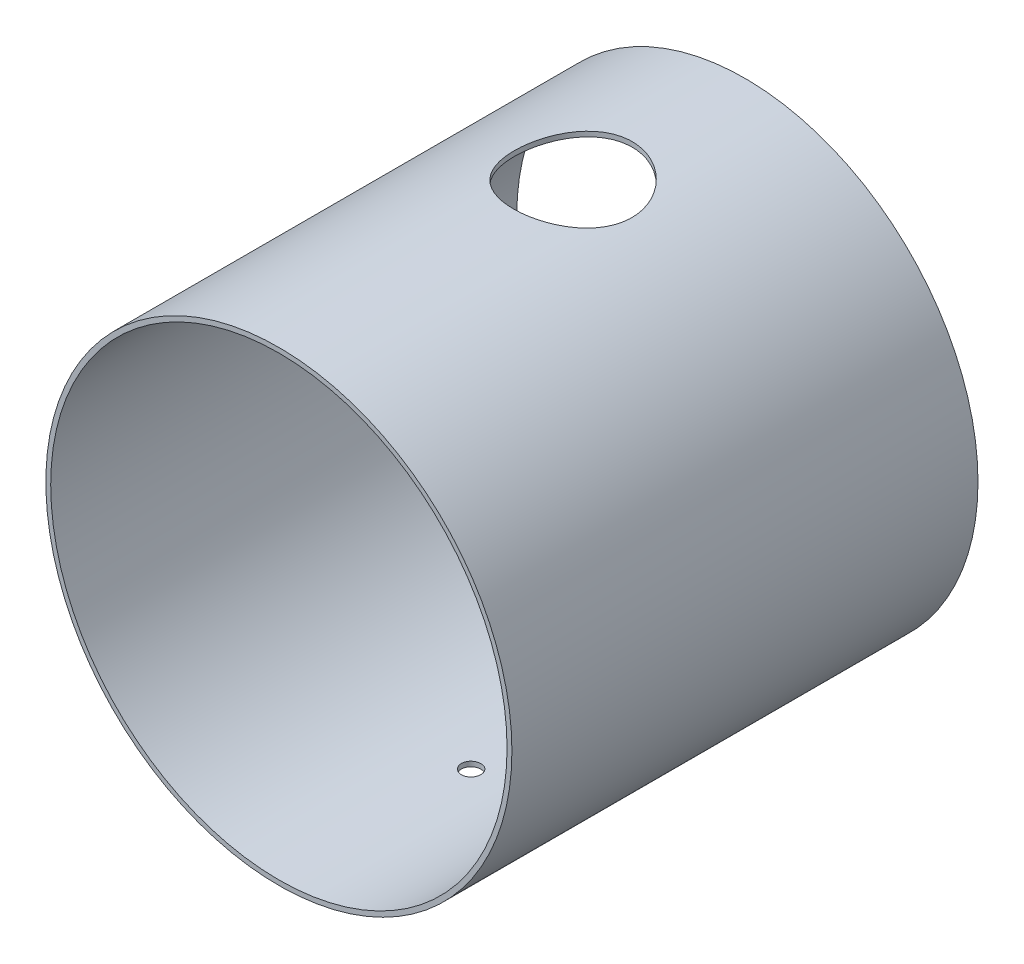
SolidWorks part; units mm, degrees
ref_plane "Front Plane" through (0, 0, 0) normal (0, 0, 1) x (1, 0, 0)
ref_plane "Top Plane" through (0, 0, 0) normal (0, 1, 0) x (1, 0, 0)
ref_plane "Right Plane" through (0, 0, 0) normal (1, 0, 0) x (0, 0, -1)
sketch "Sketch1" plane through (0, 0, 0) normal (0, 0, 1) x (1, 0, 0)
  line L0 (-149.225, 0) -> (-152.4, 0) construction
  circle A0 centre (0, 0) radius 149.225
  circle A1 centre (0, 0) radius 152.4
  dimension "OD" = 304.8
  dimension "ID" = 298.45
  dimension "Wall Thickness" = 3.175
sketch "Sketch2" plane through (0, 0, 0) normal (1, 0, 0) x (0, 0, -1)
  line L0 (-152.4, -152.4) -> (152.4, -152.4)
  line L1 (-76.2, 152.4) -> (76.2, 152.4) construction
  line L3 (-152.4, 152.4) -> (152.4, 152.4)
  point P2 (0, -152.4)
  point P3 (0, 152.4)
  point P10 (-76.2, 152.4)
  point P12 (76.2, 152.4)
  dimension "Length" = 304.8
  dimension "OD" = 304.8
  dimension "D1" = 152.4
sketch "Sketch3" plane through (0, 0, 0) normal (0, 0, 1) x (1, 0, 0)
  circle A0 centre (0, 0) radius 149.225 construction
  circle A1 centre (0, 0) radius 152.4 construction
  circle A2 centre (0, 0) radius 149.225
  circle A3 centre (0, 0) radius 152.4
extrude "Boss-Extrude1" add sketch "Sketch3" along normal mid plane 304.8
hole_wizard "Ø1.0mm Dowel Hole1" positions "3DSketch1" profile "Sketch4" hole size "Ø1.0" standard "ANSI Metric"
sketch3d "3DSketch1"
  point P0 (-1.2376, 152.395, -41.1956)
  point P1 (-1.2376, 152.395, -41.1956)
  point P3 (-1.2376, 152.395, -41.1956)
sketch "Sketch4" plane through (-1.2376, 152.395, -41.1956) normal (0, 0, 1) x (-1, -0.0081, 0)
  line L0 (0, 0) -> (0, 3.175)
  line L1 (0, 3.175) -> (38.5, 3.175)
  line L2 (38.5, 3.175) -> (38.5, 0)
  line L5 (38.5, 0) -> (0, 0)
  line L11 (0, -6.35) -> (0, 107.95) construction
  dimension "Thru Hole Dia." = 77
  dimension "Thru Hole Depth" = 3.175
hole_wizard "1/2 (0.5) Diameter Hole1" positions "3DSketch2" profile "Sketch5" hole size "1/2" standard "ANSI Inch"
sketch3d "3DSketch2"
  point P0 (-0.5472, -152.399, -42.1363)
  point P2 (0.1824, -152.3999, 26.814)
sketch "Sketch5" plane through (-0.5472, -152.399, -42.1363) normal (0, 0, 1) x (1, -0.0036, 0)
  line L0 (0, 0) -> (0, 3.175)
  line L1 (0, 3.175) -> (6.35, 3.175)
  line L2 (6.35, 3.175) -> (6.35, 0)
  line L5 (6.35, 0) -> (0, 0)
  line L11 (0, -6.35) -> (0, 107.95) construction
  dimension "Thru Hole Dia." = 12.7
  dimension "Thru Hole Depth" = 3.175
equation "\"D1@Boss-Extrude1\"=\"length@sketch2\""
equation "\"D1@Sketch2\"=\"Length@Sketch2\"*0.5"
